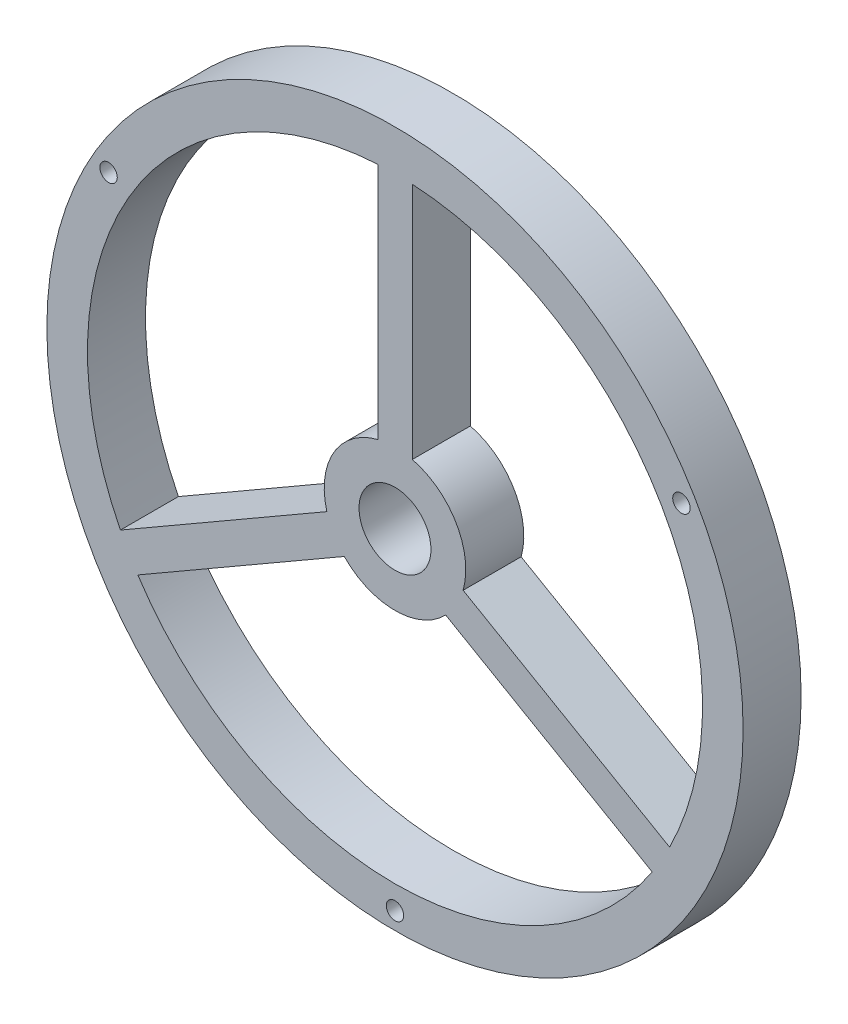
SolidWorks part; units mm, degrees
ref_plane "前视基准面" through (0, 0, 0) normal (0, 0, 1) x (1, 0, 0)
ref_plane "上视基准面" through (0, 0, 0) normal (0, 1, 0) x (1, 0, 0)
ref_plane "右视基准面" through (0, 0, 0) normal (1, 0, 0) x (0, 0, -1)
sketch "草图1" plane through (0, 0, 0) normal (0, 0, 1) x (1, 0, 0)
  line L0 (48.2965, 27.9249) -> (48.2965, 57.9249) construction
  line L1 (48.2965, 27.9249) -> (22.3157, 12.9249) construction
  line L2 (48.2965, 27.9249) -> (74.2772, 12.9249) construction
  line L3 (81.0732, 9.0013) -> (81.8232, 10.3003)
  line L7 (46.8483, 66.0915) -> (46.8483, 32.6388)
  line L11 (49.7879, 66.0915) -> (49.7879, 32.6388)
  line L12 (81.0732, 9.0013) -> (80.3232, 7.7022)
  line L13 (81.8232, 10.3003) -> (52.5654, 27.1923)
  line L14 (52.5654, 27.1923) -> (51.0654, 24.5942)
  line L15 (51.0654, 24.5942) -> (80.3232, 7.7022)
  line L16 (15.5198, 9.0013) -> (14.7698, 10.3003)
  line L17 (15.5198, 9.0013) -> (16.2698, 7.7022)
  line L18 (14.7698, 10.3003) -> (43.9274, 27.1345)
  line L19 (43.9274, 27.1345) -> (45.4274, 24.5364)
  line L20 (45.4274, 24.5364) -> (16.2698, 7.7022)
  line L21 (46.8483, 32.6388) -> (49.7879, 32.6388)
  line L22 (46.8483, 66.0915) -> (49.7879, 66.0915)
  circle A1 centre (48.2965, 27.9249) radius 3.1
  circle A2 centre (48.2965, 27.9249) radius 6.1
  circle A3 centre (48.2965, 27.9249) radius 30
  circle A4 centre (48.2965, 27.9249) radius 26.5
  dimension "D1" = 3
  dimension "D2" = 3.5
extrude "凸台-拉伸2" add sketch "草图1" along normal blind 5 contours A4 L7 A3 L18 | A4 L13 A3 L11 | A4 L20 A3 L15 | A4 L18 A3 L20 | L18 A4 L20 A2 | L7 A2 L18 L19 L20 L15 L14 L13 L11 L21 A1 | L18 A2 L20 L19 | L15 A2 L13 L14 | L11 A2 L7 L21 | L11 A4 L7 A2 | L15 A4 L13 A2 | A4 L15 A3 L13 | A4 L11 A3 L7
sketch "草图2" plane through (0, 0, 5) normal (0, 0, 1) x (1, 0, 0)
  line L0 (48.2965, 27.9249) -> (23.6148, 42.1749)
  line L1 (48.2965, 27.9249) -> (72.9782, 42.1749)
  line L2 (48.2965, 27.9249) -> (48.2965, -0.5751)
  circle A0 centre (23.6148, 42.1749) radius 0.75
  circle A1 centre (72.9782, 42.1749) radius 0.75
  circle A2 centre (48.2965, -0.5751) radius 0.75
extrude "切除-拉伸1" cut sketch "草图2" against normal blind 5
